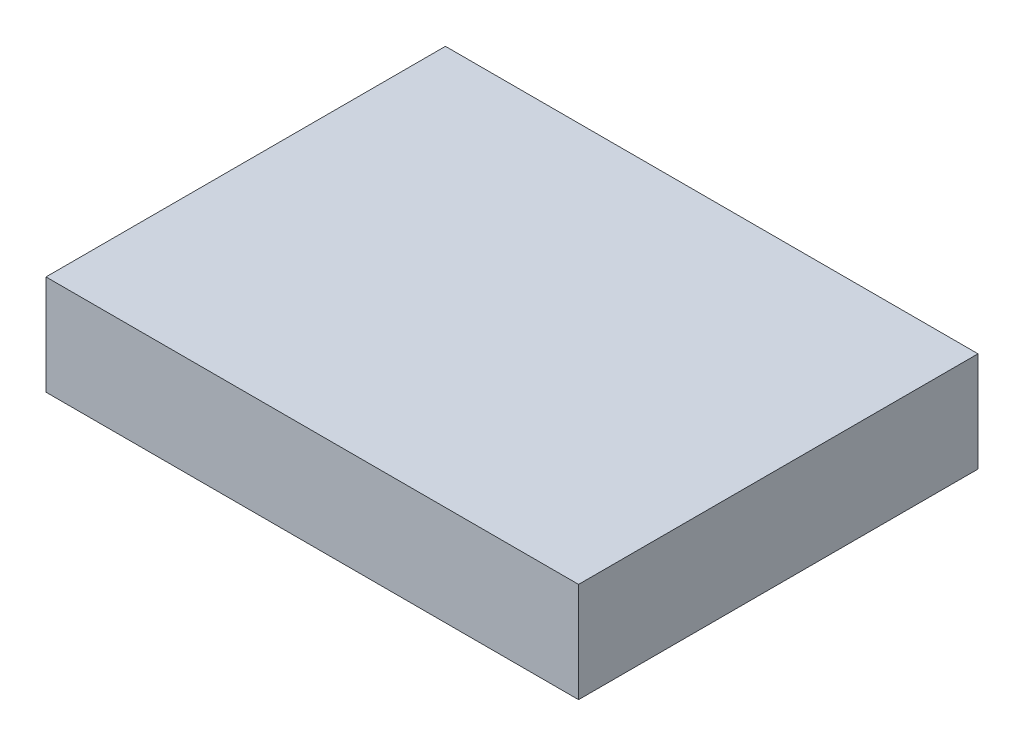
SolidWorks part; units mm, degrees
ref_plane "Front Plane" through (0, 0, 0) normal (0, 0, 1) x (1, 0, 0)
ref_plane "Top Plane" through (0, 0, 0) normal (0, 1, 0) x (1, 0, 0)
ref_plane "Right Plane" through (0, 0, 0) normal (1, 0, 0) x (0, 0, -1)
sketch "Sketch14" plane through (0, 0, 0) normal (0, 1, 0) x (1, 0, 0)
  line L1 (0, 0) -> (101.6, 0)
  line L2 (0, 0) -> (0, 76.2)
  line L3 (0, 76.2) -> (101.6, 76.2)
  line L4 (101.6, 0) -> (101.6, 76.2)
  dimension "D1" = 101.6
  dimension "D2" = 76.2
extrude "Extrude5" add sketch "Sketch14" against normal blind 19.05
